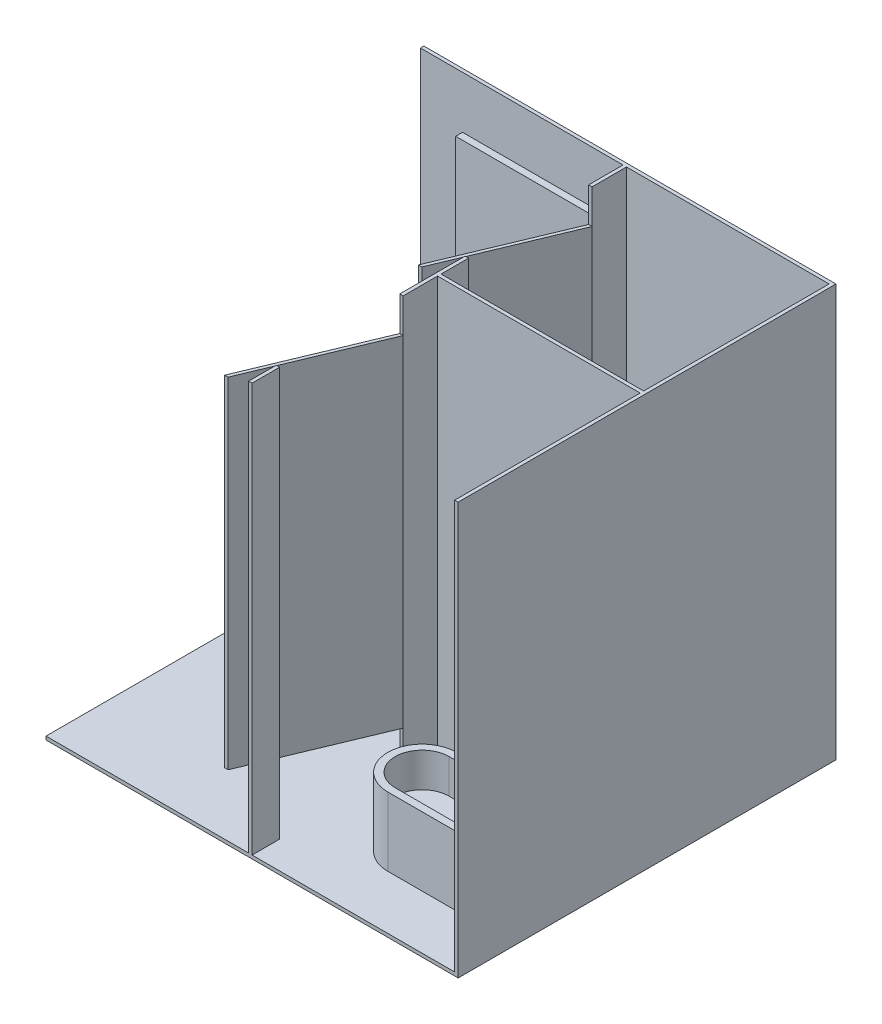
SolidWorks part; units mm, degrees
ref_plane "정면" through (0, 0, 0) normal (0, 0, 1) x (1, 0, 0)
ref_plane "윗면" through (0, 0, 0) normal (0, 1, 0) x (1, 0, 0)
ref_plane "우측면" through (0, 0, 0) normal (1, 0, 0) x (0, 0, -1)
sketch "스케치1" plane through (0, 0, 0) normal (0, 1, 0) x (1, 0, 0)
  line L1 (-60, 55) -> (60, 55)
  line L2 (-60, 55) -> (-60, -55)
  line L3 (-60, -55) -> (60, -55)
  line L4 (60, 55) -> (60, -55)
  line L5 (-60, 55) -> (60, -55) construction
  line L6 (-60, -55) -> (60, 55) construction
  point P0 (0, 0)
  dimension "D1" = 120
  dimension "D2" = 110
extrude "보스-돌출2" add sketch "스케치1" along normal blind 120
sketch "스케치2" plane through (0, 0, 55) normal (0, 0, 1) x (1, 0, 0)
  line L0 (0, 0) -> (0, 120) construction
  line L1 (-60, 120) -> (60, 120) construction
  line L3 (-59, 119) -> (59, 119)
  line L4 (-59, 119) -> (-59, 1)
  line L5 (-59, 1) -> (59, 1)
  line L6 (59, 119) -> (59, 1)
  line L7 (-59, 119) -> (59, 1) construction
  line L8 (-59, 1) -> (59, 119) construction
  point P5 (0, 60)
  dimension "D1" = 118
  dimension "D2" = 118
extrude "컷-돌출1" cut sketch "스케치2" against normal blind 109
sketch "스케치5" plane through (-60, 0, 0) normal (-1, 0, 0) x (0, 0, 1)
  line L0 (55, 120) -> (55, 119)
  line L1 (55, 120) -> (55, 0) construction
  line L2 (55, 119) -> (-54, 119)
  line L3 (-54, 119) -> (-54, 1)
  line L4 (-54, 1) -> (55, 1)
  line L5 (55, 1) -> (55, 0)
  line L6 (-55, 120) -> (-55, 0) construction
  line L7 (-55, 0) -> (55, 0) construction
  line L8 (55, 119) -> (55, 1)
  line M5 (55, 0) -> (55, 120)
  dimension "D1" = 1
  dimension "D2" = 1
  dimension "D3" = 1
extrude "컷-돌출2" cut sketch "스케치5" against normal blind 109 contours L3 L4 L2 M5
sketch "스케치6" plane through (0, 120, 0) normal (0, 1, 0) x (1, 0, 0)
  line L0 (-60, 55) -> (-60, -55) construction
  line L1 (-60, 54) -> (59, 54)
  line L2 (-60, 54) -> (-60, -55)
  line L3 (-60, -55) -> (59, -55)
  line L4 (59, 54) -> (59, -55)
  line L5 (-60, -55) -> (60, -55) construction
  line L6 (60, 55) -> (-60, 55) construction
  line L7 (60, -55) -> (60, 55) construction
  dimension "D1" = 1
  dimension "D2" = 1
extrude "컷-돌출3" cut sketch "스케치6" against normal blind 109 contours L2 L1 L4 L3
sketch "스케치7" plane through (0, 1, 0) normal (0, 1, 0) x (1, 0, 0)
  line L0 (-0.5, -55) -> (-0.5, 54) construction
  line L1 (-60, -55) -> (59, -55) construction
  line L2 (-60, 54) -> (59, 54) construction
  line L4 (-1, 54) -> (0, 54)
  line L5 (-1, 54) -> (-1, -55)
  line L6 (-1, -55) -> (0, -55)
  line L7 (0, 54) -> (0, -55)
  line L8 (-1, 54) -> (0, -55) construction
  line L9 (-1, -55) -> (0, 54) construction
  point P6 (-0.5, -0.5)
extrude "보스-돌출3" add sketch "스케치7" along normal blind 119
sketch "스케치8" plane through (0, 1, 0) normal (0, 1, 0) x (1, 0, 0)
  line L0 (-60, -0.5) -> (59, -0.5) construction
  line L1 (-60, 54) -> (-60, -55) construction
  line L2 (59, 54) -> (59, -55) construction
  line L4 (-60, 0) -> (59, 0)
  line L5 (-60, 0) -> (-60, -1)
  line L6 (-60, -1) -> (59, -1)
  line L7 (59, 0) -> (59, -1)
  line L8 (-60, 0) -> (59, -1) construction
  line L9 (-60, -1) -> (59, 0) construction
  point P6 (-0.5, -0.5)
  dimension "D1" = 1
extrude "보스-돌출5" add sketch "스케치8" along normal blind 119
sketch "스케치9" plane through (-1, 0, 0) normal (-1, 0, 0) x (0, 0, 1)
  line L0 (-54, 60.5) -> (0, 60.5) construction
  line L1 (-54, 120) -> (-54, 1) construction
  line L2 (0, 120) -> (0, 1) construction
  line L3 (-54, 120) -> (-44, 120)
  line L4 (-54, 120) -> (0, 120) construction
  line L5 (-54, 1) -> (-44, 1)
  line L6 (-44, 120) -> (-44, 110)
  line L7 (-44, 1) -> (-44, 11)
  line L8 (-44, 110) -> (-8, 110)
  line L9 (-44, 11) -> (-8, 11)
  line L10 (-8, 110) -> (-8, 120)
  line L11 (-8, 11) -> (-8, 1)
  line L12 (-8, 120) -> (0, 120)
  line L13 (-8, 1) -> (0, 1)
  line L14 (-44, 120) -> (-8, 120)
  line L15 (-44, 1) -> (-8, 1)
  dimension "D1" = 10
  dimension "D2" = 8
  dimension "D3" = 10
extrude "컷-돌출4" cut sketch "스케치9" against normal blind 39
sketch "스케치11" plane through (-1, 0, 0) normal (-1, 0, 0) x (0, 0, 1)
  line L0 (55, 60.5) -> (1, 60.5) construction
  line L1 (55, 120) -> (55, 1) construction
  line L2 (1, 1) -> (1, 120) construction
  line L3 (1, 120) -> (11, 120)
  line L4 (1, 120) -> (55, 120) construction
  line L5 (1, 1) -> (11, 1)
  line L6 (11, 120) -> (11, 110)
  line L7 (11, 1) -> (11, 11)
  line L8 (11, 110) -> (47, 110)
  line L9 (11, 11) -> (47, 11)
  line L10 (47, 110) -> (47, 120)
  line L11 (47, 11) -> (47, 1)
  line L12 (47, 120) -> (55, 120)
  line L13 (47, 1) -> (55, 1)
  line L14 (11, 120) -> (47, 120)
  line L15 (11, 1) -> (47, 1)
  line M6 (1, 1) -> (55, 1)
  line M8 (55, 120) -> (1, 120)
  dimension "D1" = 10
  dimension "D2" = 10
  dimension "D3" = 8
extrude "컷-돌출5" cut sketch "스케치11" against normal blind 39 contours L8 L10 L6 M8 | L11 L9 L7 M6
sketch "스케치12" plane through (-1, 0, 0) normal (-1, 0, 0) x (0, 0, 1)
  line L1 (-44, 110) -> (-8, 110)
  line L2 (-44, 110) -> (-44, 11)
  line L3 (-44, 11) -> (-8, 11)
  line L4 (-8, 110) -> (-8, 11)
extrude "보스-돌출6" add sketch "스케치12" along normal blind 30
sketch "스케치13" plane through (0, 110, 0) normal (0, 1, 0) x (1, 0, 0)
  line L0 (-1, 44) -> (-16, 8)
  line L1 (-31, 8) -> (-1, 8) construction
  line L2 (0, 44) -> (-15, 8)
  line L3 (-16, 8) -> (-31, 8)
  line L4 (-31, 8) -> (-31, 44)
  line L5 (-31, 44) -> (-1, 44)
  line L6 (-15, 8) -> (0, 8)
  line L7 (0, 8) -> (0, 44)
extrude "컷-돌출6" cut sketch "스케치13" against normal blind 100
sketch "스케치14" plane through (-1, 0, 0) normal (-1, 0, 0) x (0, 0, 1)
  line L1 (11, 110) -> (47, 110)
  line L2 (11, 110) -> (11, 11)
  line L3 (11, 11) -> (47, 11)
  line L4 (47, 110) -> (47, 11)
extrude "보스-돌출7" add sketch "스케치14" along normal blind 30
sketch "스케치15" plane through (0, 110, 0) normal (0, 1, 0) x (1, 0, 0)
  line L0 (-1, -11) -> (-16, -47)
  line L1 (-31, -47) -> (-1, -47) construction
  line L2 (0, -11) -> (-15, -47)
  line L3 (-16, -47) -> (-31, -47)
  line L4 (-31, -47) -> (-31, -11)
  line L5 (-31, -11) -> (-1, -11)
  line L6 (0, -11) -> (0, -47)
  line L7 (0, -47) -> (-15, -47)
extrude "컷-돌출7" cut sketch "스케치15" against normal blind 100
sketch "스케치16" plane through (0, 1, 0) normal (0, 1, 0) x (1, 0, 0)
  line L0 (-60, -0.5) -> (60, -0.5) construction
  line L1 (-60, 0) -> (-60, -1) construction
  line L2 (60, -55) -> (60, 55) construction
  line L3 (48.1469, -29.3394) -> (23.8564, -29.3394) construction
  line L4 (48.1469, -39.3394) -> (23.8564, -39.3394)
  line L5 (48.1469, -19.3394) -> (23.8564, -19.3394)
  line L6 (48.1469, 28.3394) -> (23.8564, 28.3394) construction
  line L7 (48.1469, 38.3394) -> (23.8564, 38.3394)
  line L8 (48.1469, 18.3394) -> (23.8564, 18.3394)
  arc A0 (48.1469, -39.3394) -> (48.1469, -19.3394) centre (48.1469, -29.3394) ccw
  arc A1 (23.8564, -19.3394) -> (23.8564, -39.3394) centre (23.8564, -29.3394) ccw
  arc A2 (48.1469, 38.3394) -> (48.1469, 18.3394) centre (48.1469, 28.3394) cw
  arc A3 (23.8564, 18.3394) -> (23.8564, 38.3394) centre (23.8564, 28.3394) cw
  point P8 (36.0017, -29.3394)
  point P16 (36.0017, 28.3394)
  dimension "D1" = 20
extrude "보스-돌출9" add sketch "스케치16" along normal blind 20
sketch "스케치17" plane through (0, 21, 0) normal (0, 1, 0) x (1, 0, 0)
  line L0 (-60, -0.5) -> (60, -0.5) construction
  line L1 (-60, 0) -> (-60, -1) construction
  line L2 (60, -55) -> (60, 55) construction
  line L3 (23.8564, -29.3394) -> (42.5677, -29.3394) construction
  line L4 (23.8564, -21.4748) -> (42.5677, -21.4748)
  line L5 (23.8564, -37.2041) -> (42.5677, -37.2041)
  line L6 (23.8564, 28.3394) -> (42.5677, 28.3394) construction
  line L7 (23.8564, 20.4748) -> (42.5677, 20.4748)
  line L8 (23.8564, 36.2041) -> (42.5677, 36.2041)
  arc A0 (23.8564, -21.4748) -> (23.8564, -37.2041) centre (23.8564, -29.3394) ccw
  arc A1 (42.5677, -37.2041) -> (42.5677, -21.4748) centre (42.5677, -29.3394) ccw
  arc A2 (23.8564, 20.4748) -> (23.8564, 36.2041) centre (23.8564, 28.3394) cw
  arc A3 (42.5677, 36.2041) -> (42.5677, 20.4748) centre (42.5677, 28.3394) cw
  point P9 (33.2121, -29.3394)
  point P17 (33.2121, 28.3394)
extrude "컷-돌출8" cut sketch "스케치17" against normal blind 10
sketch "스케치19" plane through (0, 11, 0) normal (0, 1, 0) x (1, 0, 0)
  line L0 (-60, -0.5) -> (60, -0.5) construction
  line L1 (-60, 0) -> (-60, -1) construction
  line L2 (60, -55) -> (60, 55) construction
  line L3 (39.6014, 28.5121) -> (44.2725, 28.5121) construction
  line L4 (39.6014, 31.1462) -> (44.2725, 31.1462)
  line L5 (39.6014, 25.878) -> (44.2725, 25.878)
  line L6 (39.6014, -29.5121) -> (44.2725, -29.5121) construction
  line L7 (39.6014, -32.1462) -> (44.2725, -32.1462)
  line L8 (39.6014, -26.878) -> (44.2725, -26.878)
  arc A0 (39.6014, 31.1462) -> (39.6014, 25.878) centre (39.6014, 28.5121) ccw
  arc A1 (44.2725, 25.878) -> (44.2725, 31.1462) centre (44.2725, 28.5121) ccw
  arc A2 (39.6014, -32.1462) -> (39.6014, -26.878) centre (39.6014, -29.5121) cw
  arc A3 (44.2725, -26.878) -> (44.2725, -32.1462) centre (44.2725, -29.5121) cw
  point P8 (41.9369, 28.5121)
  point P16 (41.9369, -29.5121)
extrude "컷-돌출9" cut sketch "스케치19" against normal blind 10
sketch "스케치22" plane through (0, 21, 0) normal (0, 1, 0) x (1, 0, 0)
  line L0 (-60, -0.5) -> (60, -0.5) construction
  line L1 (-60, 0) -> (-60, -1) construction
  line L2 (60, -55) -> (60, 55) construction
  line L3 (50.7478, -38.9953) -> (50.7478, -19.7253)
  line L4 (50.7478, 37.9953) -> (51.6734, 37.9953)
  line L5 (50.7478, 37.9953) -> (50.7478, 18.7253)
  line L6 (50.7478, 18.7253) -> (51.6734, 18.7253)
  line L7 (51.6734, 37.9953) -> (51.6734, 18.7253)
  line L8 (50.7478, -38.9953) -> (51.6734, -38.9953)
  line L9 (51.6734, -38.9953) -> (51.6734, -19.7253)
  line L10 (50.7478, -19.7253) -> (51.6734, -19.7253)
  arc A0 (48.1469, 18.3394) -> (48.1469, 38.3394) centre (48.1469, 28.3394) ccw construction
extrude "보스-돌출10" add sketch "스케치22" along normal blind 30
sketch "스케치26" plane through (50.7478, 0, 0) normal (-1, 0, 0) x (0, 0, 1)
  line L0 (0.5, 120) -> (0.5, 0) construction
  line L1 (0, 120) -> (1, 120) construction
  line L2 (-55, 0) -> (55, 0) construction
  line L3 (29.3603, 21) -> (29.3603, 41.1639) construction
  line L4 (19.7253, 21) -> (38.9953, 21) construction
  line L5 (19.5767, 21) -> (19.5767, 41.1639)
  line L6 (39.1439, 21) -> (39.1439, 41.1639)
  line L7 (-28.3603, 21) -> (-28.3603, 41.1639) construction
  line L8 (-18.5767, 21) -> (-18.5767, 41.1639)
  line L9 (-38.1439, 21) -> (-38.1439, 41.1639)
  line L10 (39.1439, 41.1639) -> (39.1439, 57.4163)
  line L11 (-38.1439, 41.1639) -> (-38.1439, 57.4163)
  line L12 (39.1439, 57.4163) -> (19.5767, 57.4163)
  line L13 (-38.1439, 57.4163) -> (-18.5767, 57.4163)
  line L14 (19.5767, 57.4163) -> (19.5767, 41.1639)
  line L15 (-18.5767, 57.4163) -> (-18.5767, 41.1639)
  arc A0 (19.5767, 21) -> (39.1439, 21) centre (29.3603, 21) ccw
  arc A1 (39.1439, 41.1639) -> (19.5767, 41.1639) centre (29.3603, 41.1639) ccw
  arc A2 (-18.5767, 21) -> (-38.1439, 21) centre (-28.3603, 21) cw
  arc A3 (-38.1439, 41.1639) -> (-18.5767, 41.1639) centre (-28.3603, 41.1639) cw
  point P10 (29.3603, 31.0819)
  point P18 (-28.3603, 31.0819)
  line M7 (38.9953, 21) -> (38.9953, 51)
  line M8 (38.9953, 51) -> (19.7253, 51)
  line M9 (19.7253, 51) -> (19.7253, 21)
extrude "컷-돌출14" cut sketch "스케치26" against normal blind 5 contours A1 M7 M8 M9 | L11 A3 L15 L13
sketch "스케치27" plane through (0, 1, 0) normal (0, 1, 0) x (1, 0, 0)
  line L0 (-60, 54) -> (-1, 54) construction
  line L1 (-30.5, 54) -> (-30.5, 44) construction
  circle A0 centre (-30.5, 44) radius 8
  dimension "D1" = 10
extrude "보스-돌출14" add sketch "스케치27" along normal blind 40
sketch "스케치29" plane through (0, 41, 0) normal (0, 1, 0) x (1, 0, 0)
  circle A0 centre (-30.5, 42.1865) radius 5.3814
extrude "컷-돌출15" cut sketch "스케치29" against normal blind 5
sketch "스케치30" plane through (0, 41, 0) normal (0, 1, 0) x (1, 0, 0)
  circle A0 centre (-30.5, 49.6747) radius 1.0162
extrude "보스-돌출15" add sketch "스케치30" along normal blind 10
sketch "스케치31" plane through (0, 51, 0) normal (0, 1, 0) x (1, 0, 0)
  line L0 (-30.5, 49.6747) -> (-30.5, 46.0559) construction
  line L1 (-29.5037, 49.6747) -> (-29.5037, 46.0559)
  line L2 (-31.4963, 49.6747) -> (-31.4963, 46.0559)
  arc A0 (-29.5037, 49.6747) -> (-31.4963, 49.6747) centre (-30.5, 49.6747) ccw
  arc A1 (-31.4963, 46.0559) -> (-29.5037, 46.0559) centre (-30.5, 46.0559) ccw
  point P3 (-30.5, 47.8653)
extrude "보스-돌출16" add sketch "스케치31" along normal blind 3
sketch "스케치32" plane through (0, 0, -54) normal (0, 0, 1) x (1, 0, 0)
  line L1 (-47.7212, 104.8707) -> (-3.5321, 104.8707)
  line L2 (-47.7212, 104.8707) -> (-47.7212, 55.7521)
  line L3 (-47.7212, 55.7521) -> (-3.5321, 55.7521)
  line L4 (-3.5321, 104.8707) -> (-3.5321, 55.7521)
extrude "보스-돌출17" add sketch "스케치32" along normal blind 2
sketch "스케치33" plane through (0, 0, 1) normal (0, 0, 1) x (1, 0, 0)
  line L1 (-60, 120) -> (-1, 120)
  line L2 (-60, 120) -> (-60, 1)
  line L3 (-60, 1) -> (-1, 1)
  line L4 (-1, 120) -> (-1, 1)
extrude "컷-돌출16" cut sketch "스케치33" against normal blind 10
